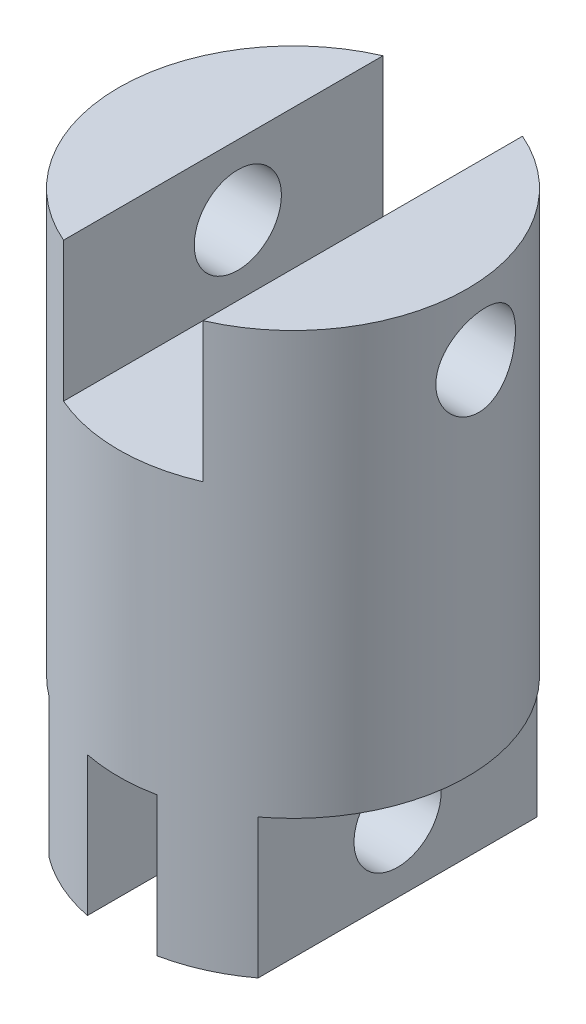
SolidWorks part; units mm, degrees
ref_plane "Front Plane" through (0, 0, 0) normal (0, 0, 1) x (1, 0, 0)
ref_plane "Top Plane" through (0, 0, 0) normal (0, 1, 0) x (1, 0, 0)
ref_plane "Right Plane" through (0, 0, 0) normal (1, 0, 0) x (0, 0, -1)
sketch "Sketch1" plane through (0, 0, 0) normal (0, 1, 0) x (1, 0, 0)
  circle A0 centre (0, 0) radius 12.7
  dimension "D1" = 25.4
extrude "Boss-Extrude1" add sketch "Sketch1" along normal blind 40.9448
sketch "Sketch2" plane through (0, 40.9448, 0) normal (0, 1, 0) x (1, 0, 0)
  line L0 (5.08, 11.6397) -> (5.08, -11.6397)
  line L1 (-5.08, 11.6397) -> (-5.08, -11.6397)
  arc A0 (-5.08, -11.6397) -> (5.08, -11.6397) centre (0, 0) ccw
  arc A1 (5.08, 11.6397) -> (-5.08, 11.6397) centre (0, 0) ccw
  dimension "D2" = 25.4
  dimension "D1" = 5.08
  dimension "D3" = 5.08
extrude "Cut-Extrude1" cut sketch "Sketch2" against normal blind 10.16
sketch "Sketch3" plane through (0, 0, 0) normal (0, -1, 0) x (1, 0, 0)
  line L0 (-2.54, 12.4434) -> (-2.54, -12.4434)
  line L1 (-7.62, 10.16) -> (-7.62, -10.16)
  line L2 (2.54, 12.4434) -> (2.54, -12.4434)
  line L3 (7.62, 10.16) -> (7.62, -10.16)
  arc A0 (-7.62, 10.16) -> (-7.62, -10.16) centre (0, 0) ccw
  arc A1 (-2.54, -12.4434) -> (2.54, -12.4434) centre (0, 0) ccw
  arc A2 (7.62, -10.16) -> (7.62, 10.16) centre (0, 0) ccw
  arc A3 (2.54, 12.4434) -> (-2.54, 12.4434) centre (0, 0) ccw
  dimension "D1" = 25.4
  dimension "D2" = 2.54
  dimension "D3" = 5.08
  dimension "D4" = 2.54
  dimension "D5" = 5.08
extrude "Cut-Extrude2" cut sketch "Sketch3" against normal blind 10.16
sketch "Sketch4" plane through (-5.08, 0, 0) normal (1, 0, 0) x (0, 0, -1)
  line L0 (11.6397, 40.9448) -> (-11.6397, 40.9448) construction
  line L5 (10.16, 0) -> (-10.16, 0) construction
  circle A0 centre (1.0603, 35.8648) radius 3.175
  circle A2 centre (0, 5.08) radius 3.175
  dimension "D1" = 6.35
  dimension "D3" = 6.35
  dimension "D2" = 5.08
  dimension "D4" = 5.08
extrude "Cut-Extrude3" cut sketch "Sketch4" against normal through all both and the other way through all
sketch "Sketch5" plane through (0, 30.7848, 0) normal (0, 1, 0) x (1, 0, 0)
  circle A0 centre (0, 0) radius 2.54
  dimension "D1" = 5.08
extrude "Cut-Extrude4" cut sketch "Sketch5" against normal through all
